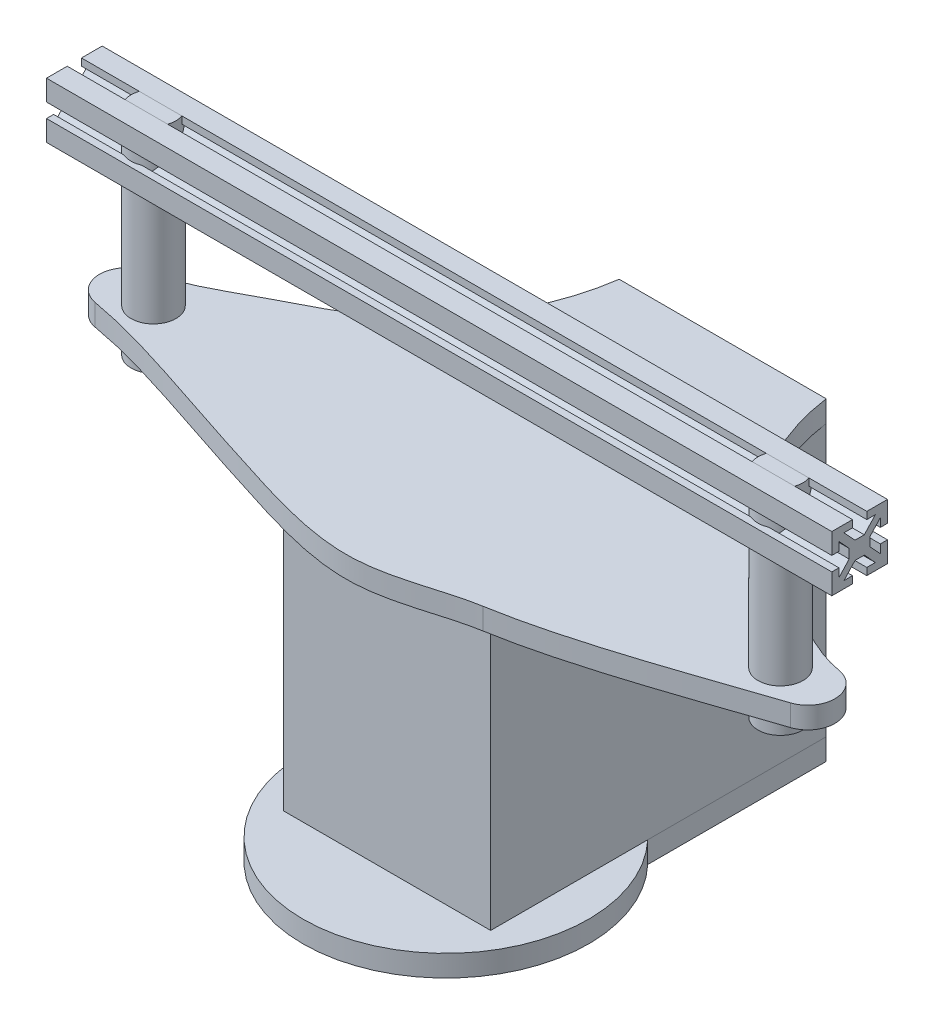
SolidWorks part; units mm, degrees
ref_plane "Front Plane" through (0, 0, 0) normal (0, 0, 1) x (1, 0, 0)
ref_plane "Top Plane" through (0, 0, 0) normal (0, 1, 0) x (1, 0, 0)
ref_plane "Right Plane" through (0, 0, 0) normal (1, 0, 0) x (0, 0, -1)
sketch "Sketch1" plane through (0, 0, 0) normal (0, 1, 0) x (1, 0, 0)
  line L1 (-14.5, 38.775) -> (14.5, 38.775)
  line L2 (-14.5, 38.775) -> (-14.5, 13.775)
  line L3 (14.5, 38.775) -> (14.5, 13.775)
  arc A0 (-14.5, 13.775) -> (14.5, 13.775) centre (0, 0) ccw
  dimension "D1" = 40
  dimension "D3" = 25
  dimension "D2" = 29
extrude "Boss-Extrude1" add sketch "Sketch1" along normal blind 3
sketch "Sketch2" plane through (0, 3, 0) normal (0, 1, 0) x (1, 0, 0)
  line L0 (14.5, 38.775) -> (-14.5, 38.775) construction
  line L1 (14.5, 38.775) -> (-14.5, 38.775)
  line L2 (14.5, 38.775) -> (14.5, -8.225)
  line L3 (14.5, -8.225) -> (-14.5, -8.225)
  line L4 (-14.5, -8.225) -> (-14.5, 38.775)
  dimension "D1" = 47
extrude "Boss-Extrude2" add sketch "Sketch2" along normal blind 38 separate body
sketch "Sketch3" plane through (0, 41, 0) normal (0, 1, 0) x (1, 0, 0)
  line L0 (0, 0) -> (0, 41.5082) construction
  line L1 (0, 38.775) -> (51.5, 38.775) construction
  line L2 (0, 38.775) -> (-51.5, 38.775) construction
  line L3 (-51.5, 38.775) -> (-51.5, -13.7185) construction
  line L4 (14.5, -8.225) -> (14.5, 38.775)
  line L5 (14.5, 38.775) -> (-14.5, 38.775)
  line L6 (-14.5, 38.775) -> (-14.5, -8.225)
  line L7 (-14.5, -8.225) -> (14.5, -8.225)
  line L9 (14.5, 38.775) -> (-14.5, 38.775)
  line L12 (51.5, 38.775) -> (51.5, -13.7185) construction
  arc A1 (-51.5, -0.4432) -> (-51.0523, -0.5411) centre (-27.4726, 108.3748) ccw
  arc A2 (-48.3417, 6.7297) -> (-48.4033, -0.7384) centre (-47.707, 2.9901) ccw
  arc A3 (48.3417, 6.7297) -> (48.9058, -0.6085) centre (47.707, 2.9901) cw
  spline S0 degree 3 poles (-14.5, 38.775) (-15.568, 30.9338) (-22.2201, 18.6152) (-37.2035, 11.889) (-44.6391, 7.3581) (-48.3417, 6.7297) knots 0 0 0 0 0.490599 0.765051 1 1 1 1
  spline S1 degree 3 poles (14.5, 38.775) (15.568, 30.9338) (22.2201, 18.6152) (37.2035, 11.889) (44.6391, 7.3581) (48.3417, 6.7297) knots 0 0 0 0 0.490599 0.765051 1 1 1 1
  spline S2 degree 3 poles (-48.4033, -0.7384) (-46.7221, -1.0524) (-39.3644, -2.5606) (-22.6683, -8.6543) (1.6125, -15.7473) (10.7284, -11.256) (15.6316, -10.4326) knots 0.248885 0.248885 0.248885 0.248885 0.339972 0.630083 0.771871 0.935575 0.935575 0.935575 0.935575
  spline S3 degree 3 poles (15.6316, -10.4326) (24.7523, -8.901) (37.1088, -4.5964) (47.6245, -1.0353) (48.9058, -0.6085) knots 0.030068 0.030068 0.030068 0.030068 0.543781 0.617486 0.617486 0.617486 0.617486
  line M12 (14.5, -8.225) -> (14.5, 38.775)
  line M13 (14.5, 38.775) -> (-14.5, 38.775)
  line M14 (-14.5, 38.775) -> (-14.5, -8.225)
  line M15 (-14.5, -8.225) -> (14.5, -8.225)
  dimension "D2" = 51.5
  dimension "D3" = 103
  dimension "D4" = 52.5101
  dimension "D5" = 48.8186
  dimension "D6" = 26.7622
  dimension "D7" = 41.1405
  dimension "D1" = 0
extrude "Boss-Extrude3" add sketch "Sketch3" along normal blind 3 contours S2 S3 A3 S1 S0 A2 M12 M15 M14 | M15 M12 M13 M14
sketch "Sketch4" plane through (0, 0, 0) normal (0, -1, 0) x (1, 0, 0)
  circle A0 centre (0, 0) radius 7
  dimension "D1" = 14
extrude "Cut-Extrude2" cut sketch "Sketch4" against normal blind 2
sketch "Sketch5" plane through (0, 44, 0) normal (0, 1, 0) x (1, 0, 0)
  line L0 (0, 0) -> (0, 51.8232) construction
  circle A0 centre (-43.9141, 2.9588) radius 3.15
  arc A1 (-48.3417, 6.7297) -> (-48.4033, -0.7384) centre (-47.707, 2.9901) ccw construction
  circle A2 centre (43.9141, 2.9588) radius 3.15
  dimension "D1" = 6.3
extrude "Boss-Extrude4" add sketch "Sketch5" along normal blind 24 and the other way blind 6
sketch "Sketch6" plane through (0, 0, 0) normal (1, 0, 0) x (0, 0, -1)
  line L0 (3.9588, 60.2) -> (3.9588, 61.2)
  line L1 (-0.9412, 68) -> (1.9588, 68)
  line L2 (-0.9412, 68) -> (-0.9412, 65.1)
  line L3 (3.9588, 60.2) -> (6.8588, 60.2)
  line L4 (6.8588, 63.1) -> (6.8588, 60.2)
  line L5 (6.1088, 68) -> (-0.1912, 68) construction
  line L6 (6.1088, 68) -> (3.9588, 68)
  line L7 (3.9588, 61.2) -> (5.1512, 61.2)
  line L8 (5.1512, 61.2) -> (3.6088, 62.8691)
  line L9 (5.8588, 61.9077) -> (4.4336, 63.45)
  line L10 (5.8588, 61.9077) -> (5.8588, 63.1)
  line L11 (5.8588, 63.1) -> (6.8588, 63.1)
  line L12 (6.8588, 63.1) -> (6.8588, 68) construction
  line L13 (-0.9412, 60.2) -> (3.9588, 60.2) construction
  line L14 (2.9588, 68) -> (2.9588, 60.2) construction
  line L15 (2.9588, 64.1) -> (9.3219, 64.1) construction
  line L16 (4.4336, 63.45) -> (4.4336, 64.75)
  line L17 (3.6088, 62.8691) -> (2.3088, 62.8691)
  line L18 (3.6088, 65.3309) -> (2.3088, 65.3309)
  line L19 (5.8588, 66.2923) -> (5.8588, 65.1)
  line L20 (5.8588, 66.2923) -> (4.4336, 64.75)
  line L21 (5.1512, 67) -> (3.6088, 65.3309)
  line L22 (3.9588, 67) -> (5.1512, 67)
  line L23 (3.9588, 68) -> (3.9588, 67)
  line L24 (3.9588, 68) -> (6.8588, 68)
  line L25 (6.8588, 65.1) -> (6.8588, 68)
  line L26 (1.484, 63.45) -> (1.484, 64.75)
  line L27 (1.9588, 68) -> (1.9588, 67)
  line L28 (1.9588, 67) -> (0.7665, 67)
  line L29 (0.7665, 67) -> (2.3088, 65.3309)
  line L30 (0.0588, 66.2923) -> (1.484, 64.75)
  line L31 (0.0588, 66.2923) -> (0.0588, 65.1)
  line L32 (-0.9412, 65.1) -> (-0.9412, 68)
  line L33 (0.0588, 63.1) -> (-0.9412, 63.1)
  line L34 (0.0588, 61.9077) -> (0.0588, 63.1)
  line L35 (0.0588, 61.9077) -> (1.484, 63.45)
  line L36 (0.7665, 61.2) -> (2.3088, 62.8691)
  line L37 (1.9588, 61.2) -> (0.7665, 61.2)
  line L38 (1.9588, 60.2) -> (1.9588, 61.2)
  line L39 (1.9588, 60.2) -> (-0.9412, 60.2)
  line L40 (-0.9412, 63.1) -> (-0.9412, 60.2)
  line L41 (0.0588, 65.1) -> (-0.9412, 65.1)
  line L42 (-0.9412, 63.1) -> (-0.9412, 60.2)
  line L43 (3.9588, 68) -> (6.8588, 68)
  line L44 (1.9588, 68) -> (-0.1912, 68)
  line L45 (6.8588, 65.1) -> (5.8588, 65.1)
  line L47 (6.1088, 44) -> (6.1088, 68) construction
  point P24 (4.4336, 64.1)
  point P31 (2.9588, 62.8691)
  point P34 (2.9588, 65.3309)
  dimension "D1" = 7.8
  dimension "D2" = 1
  dimension "D3" = 2
  dimension "D4" = 1
  dimension "D5" = 1
  dimension "D6" = 1.3
  dimension "D7" = 2.1
  dimension "D9" = 2.15
extrude "Boss-Extrude5" add sketch "Sketch6" along normal blind 55 and the other way blind 55 separate body contours L45 L25 L24 L6 L23 L22 L21 L18 L29 L28 L27 L1 L2 L41 L31 L30 L26 L35 L34 L33 L40 L39 L38 L37 L36 L17 L8 L7 L0 L3 L4 L11 L10 L9 L16 L20 L19
ref_point "Point1"
